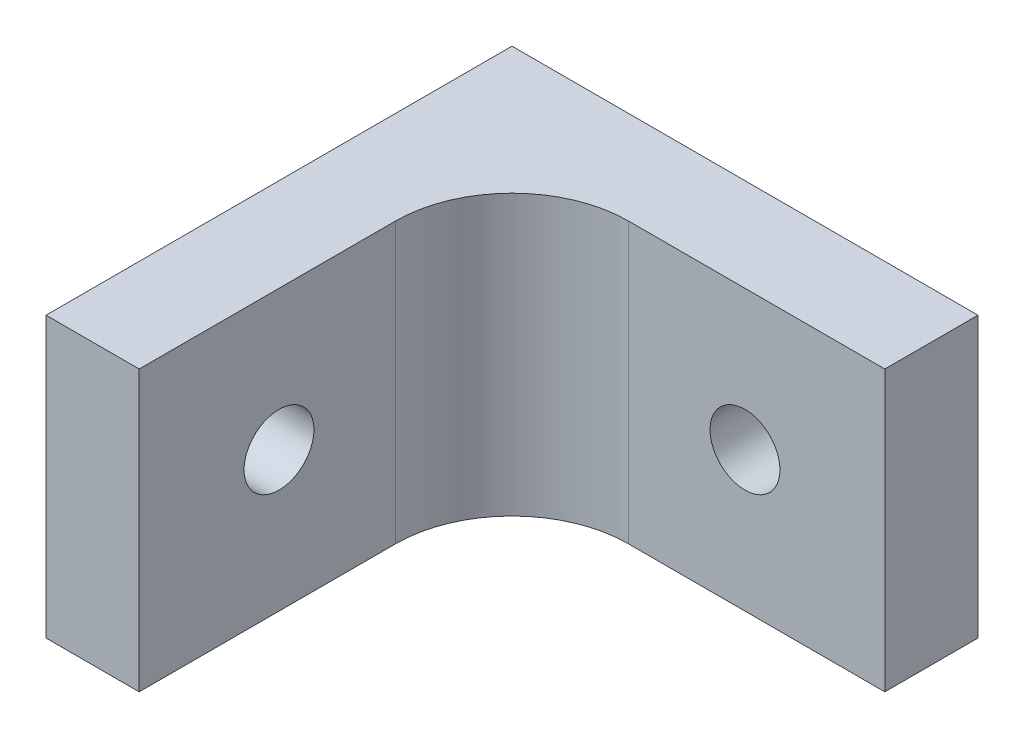
SolidWorks part; units mm, degrees
ref_plane "Front Plane" through (0, 0, 0) normal (0, 0, 1) x (1, 0, 0)
ref_plane "Top Plane" through (0, 0, 0) normal (0, 1, 0) x (1, 0, 0)
ref_plane "Right Plane" through (0, 0, 0) normal (1, 0, 0) x (0, 0, -1)
sketch "Sketch1" plane through (0, 0, 0) normal (0, 0, 1) x (1, 0, 0)
  line L0 (-3, -6) -> (-3, -3) construction
  line L1 (0, -6) -> (-10, -6)
  line L2 (0, -6) -> (0, 0)
  line L3 (0, 0) -> (-10, 0)
  line L4 (-10, -6) -> (-10, 0)
  line L5 (-3, -3) -> (0, -3) construction
  circle A0 centre (-3, -3) radius 0.75
  dimension "D5" = 1.5
  dimension "D1" = 10
  dimension "D2" = 6
  dimension "D3" = 3
  dimension "D4" = 3
extrude "Boss-Extrude1" add sketch "Sketch1" along normal blind 2
sketch "Sketch2" plane through (-10, 0, 0) normal (-1, 0, 0) x (0, 0, 1)
  line L0 (7, -3) -> (10, -3) construction
  line L1 (0, 0) -> (10, 0)
  line L2 (0, 0) -> (0, -6)
  line L3 (0, -6) -> (10, -6)
  line L4 (10, 0) -> (10, -6)
  line L5 (7, -3) -> (7, 0) construction
  circle A2 centre (7, -3) radius 0.75
  dimension "D5" = 1.5
  dimension "D1" = 6
  dimension "D2" = 10
  dimension "D3" = 3
  dimension "D4" = 3
extrude "Boss-Extrude2" add sketch "Sketch2" against normal blind 2
fillet "Fillet2" radius 2.5 1 edges at (-8, -3, 2)
